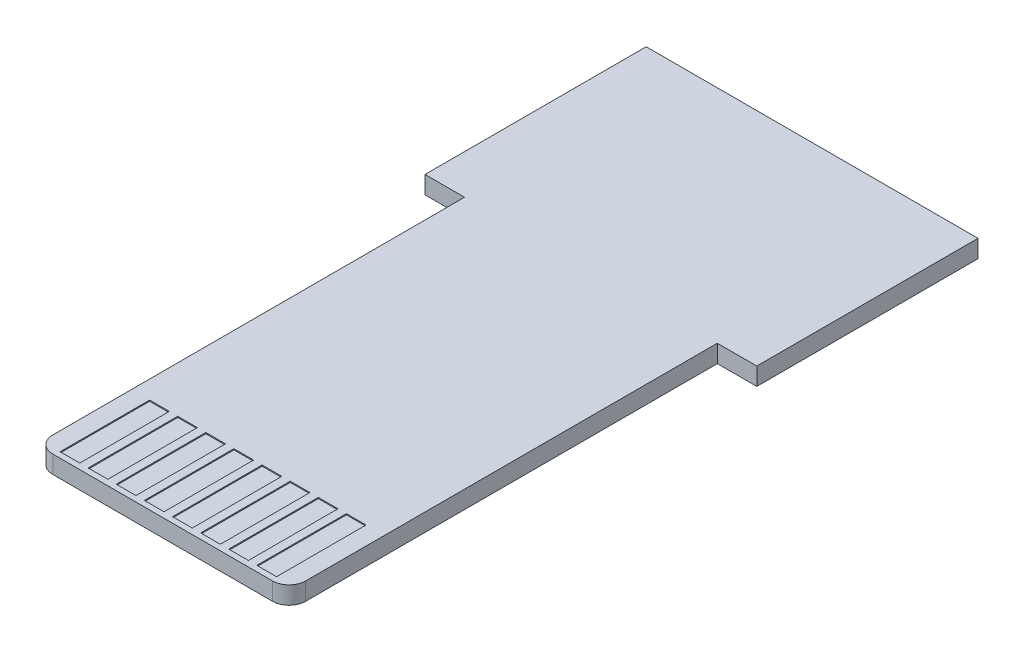
SolidWorks part; units mm, degrees
material "丙烯酸(中高冲击)"
ref_plane "前视基准面" through (0, 0, 0) normal (0, 0, 1) x (1, 0, 0)
ref_plane "上视基准面" through (0, 0, 0) normal (0, 1, 0) x (1, 0, 0)
ref_plane "右视基准面" through (0, 0, 0) normal (1, 0, 0) x (0, 0, -1)
other "Configuration Table"
sketch "草图1" plane through (0, 0, 0) normal (0, 1, 0) x (1, 0, 0)
  line L0 (11.43, -10) -> (15, -10)
  line L1 (-15, 10) -> (15, 10)
  line L2 (-15, 10) -> (-15, -10)
  line L3 (-15, -10) -> (-11.43, -10)
  line L4 (15, 10) -> (15, -10)
  line L5 (-15, 10) -> (15, -10) construction
  line L6 (-15, -10) -> (15, 10) construction
  line L8 (-11.43, -10) -> (-11.43, -47.22)
  line L9 (-9.93, -48.72) -> (9.93, -48.72)
  line L10 (11.43, -10) -> (11.43, -47.22)
  arc A0 (-11.43, -47.22) -> (-9.93, -48.72) centre (-9.93, -47.22) ccw
  arc A1 (9.93, -48.72) -> (11.43, -47.22) centre (9.93, -47.22) ccw
  point P0 (0, 0)
  point P10 (0, -48.72)
  dimension "D5" = 3
  dimension "D6" = 3
  dimension "D1" = 30
  dimension "D2" = 20
  dimension "D3" = 38.72
  dimension "D4" = 22.86
extrude "凸台-拉伸1" add sketch "草图1" along normal blind 1.6
sketch "草图3" plane through (0, 0, 0) normal (0, 1, 0) x (1, 0, 0)
  line L0 (0, -1000) -> (0, 49000) construction
  line L1 (-9.93, -48.72) -> (9.93, -48.72) construction
  line L2 (-2.165, -40.11) -> (-0.385, -40.11)
  line L3 (-2.165, -40.11) -> (-2.165, -48.21)
  line L4 (-2.165, -48.21) -> (-0.385, -48.21)
  line L5 (-0.385, -40.11) -> (-0.385, -48.21)
  line L6 (0.385, -40.11) -> (2.165, -40.11)
  line L7 (0.385, -40.11) -> (0.385, -48.21)
  line L8 (0.385, -48.21) -> (2.165, -48.21)
  line L9 (2.165, -40.11) -> (2.165, -48.21)
  line L10 (-4.705, -40.11) -> (-2.925, -40.11)
  line L11 (-4.705, -40.11) -> (-4.705, -48.21)
  line L12 (-4.705, -48.21) -> (-2.925, -48.21)
  line L13 (-2.925, -40.11) -> (-2.925, -48.21)
  line L14 (-7.245, -40.11) -> (-5.465, -40.11)
  line L15 (-7.245, -40.11) -> (-7.245, -48.21)
  line L16 (-7.245, -48.21) -> (-5.465, -48.21)
  line L17 (-5.465, -40.11) -> (-5.465, -48.21)
  line L18 (-9.785, -40.11) -> (-8.005, -40.11)
  line L19 (-9.785, -40.11) -> (-9.785, -48.21)
  line L20 (-9.785, -48.21) -> (-8.005, -48.21)
  line L21 (-8.005, -40.11) -> (-8.005, -48.21)
  line L22 (-2.165, -40.11) -> (-4.705, -40.11) construction
  line L23 (2.925, -40.11) -> (4.705, -40.11)
  line L24 (2.925, -40.11) -> (2.925, -48.21)
  line L25 (2.925, -48.21) -> (4.705, -48.21)
  line L26 (4.705, -40.11) -> (4.705, -48.21)
  line L27 (5.465, -40.11) -> (7.245, -40.11)
  line L28 (5.465, -40.11) -> (5.465, -48.21)
  line L29 (5.465, -48.21) -> (7.245, -48.21)
  line L30 (7.245, -40.11) -> (7.245, -48.21)
  line L31 (8.005, -40.11) -> (9.785, -40.11)
  line L32 (8.005, -40.11) -> (8.005, -48.21)
  line L33 (8.005, -48.21) -> (9.785, -48.21)
  line L34 (9.785, -40.11) -> (9.785, -48.21)
  line L35 (0.385, -40.11) -> (2.925, -40.11) construction
  dimension "D1" = 1.78
  dimension "D2" = 8.1
  dimension "D3" = 8.1
  dimension "D4" = 1.78
  dimension "D5" = 0.51
  dimension "D6" = 0.51
  dimension "D7" = 0.77
  dimension "D8" = 4
  dimension "D9" = 2.54
  dimension "D11" = 2.54
  dimension "D10" = 4
extrude "切除-拉伸1" cut sketch "草图3" against normal blind 0.1 from surface at 1.6 starting at face at (0, 1.6, 21.2501)
sketch "草图4" plane through (0, 0, 0) normal (0, 1, 0) x (1, 0, 0)
  line L4 (2.165, -40.11) -> (0.385, -40.11)
  line L5 (2.165, -48.21) -> (2.165, -40.11)
  line L6 (0.385, -48.21) -> (2.165, -48.21)
  line L7 (0.385, -40.11) -> (0.385, -48.21)
  line L8 (2.165, -40.11) -> (0.385, -40.11)
  line L9 (2.165, -48.21) -> (2.165, -40.11)
  line L10 (0.385, -48.21) -> (2.165, -48.21)
  line L11 (0.385, -40.11) -> (0.385, -48.21)
  line L12 (-0.385, -40.11) -> (-2.165, -40.11)
  line L13 (-0.385, -48.21) -> (-0.385, -40.11)
  line L14 (-2.165, -48.21) -> (-0.385, -48.21)
  line L15 (-2.165, -40.11) -> (-2.165, -48.21)
  line L16 (-0.385, -40.11) -> (-2.165, -40.11)
  line L17 (-0.385, -48.21) -> (-0.385, -40.11)
  line L18 (-2.165, -48.21) -> (-0.385, -48.21)
  line L19 (-2.165, -40.11) -> (-2.165, -48.21)
  line L20 (-8.005, -40.11) -> (-9.785, -40.11)
  line L21 (-8.005, -48.21) -> (-8.005, -40.11)
  line L22 (-9.785, -48.21) -> (-8.005, -48.21)
  line L23 (-9.785, -40.11) -> (-9.785, -48.21)
  line L24 (-8.005, -40.11) -> (-9.785, -40.11)
  line L25 (-8.005, -48.21) -> (-8.005, -40.11)
  line L26 (-9.785, -48.21) -> (-8.005, -48.21)
  line L27 (-9.785, -40.11) -> (-9.785, -48.21)
  line L28 (-5.465, -40.11) -> (-7.245, -40.11)
  line L29 (-5.465, -48.21) -> (-5.465, -40.11)
  line L30 (-7.245, -48.21) -> (-5.465, -48.21)
  line L31 (-7.245, -40.11) -> (-7.245, -48.21)
  line L32 (-5.465, -40.11) -> (-7.245, -40.11)
  line L33 (-5.465, -48.21) -> (-5.465, -40.11)
  line L34 (-7.245, -48.21) -> (-5.465, -48.21)
  line L35 (-7.245, -40.11) -> (-7.245, -48.21)
  line L36 (-2.925, -40.11) -> (-4.705, -40.11)
  line L37 (-4.705, -40.11) -> (-4.705, -48.21)
  line L38 (-4.705, -48.21) -> (-2.925, -48.21)
  line L39 (-2.925, -48.21) -> (-2.925, -40.11)
  line L40 (-2.925, -40.11) -> (-4.705, -40.11)
  line L41 (-4.705, -40.11) -> (-4.705, -48.21)
  line L42 (-4.705, -48.21) -> (-2.925, -48.21)
  line L43 (-2.925, -48.21) -> (-2.925, -40.11)
  line L44 (9.785, -40.11) -> (8.005, -40.11)
  line L45 (9.785, -48.21) -> (9.785, -40.11)
  line L46 (8.005, -48.21) -> (9.785, -48.21)
  line L47 (8.005, -40.11) -> (8.005, -48.21)
  line L48 (9.785, -40.11) -> (8.005, -40.11)
  line L49 (9.785, -48.21) -> (9.785, -40.11)
  line L50 (8.005, -48.21) -> (9.785, -48.21)
  line L51 (8.005, -40.11) -> (8.005, -48.21)
  line L52 (7.245, -40.11) -> (5.465, -40.11)
  line L53 (7.245, -48.21) -> (7.245, -40.11)
  line L54 (5.465, -48.21) -> (7.245, -48.21)
  line L55 (5.465, -40.11) -> (5.465, -48.21)
  line L56 (7.245, -40.11) -> (5.465, -40.11)
  line L57 (7.245, -48.21) -> (7.245, -40.11)
  line L58 (5.465, -48.21) -> (7.245, -48.21)
  line L59 (5.465, -40.11) -> (5.465, -48.21)
  line L60 (4.705, -40.11) -> (2.925, -40.11)
  line L61 (2.925, -40.11) -> (2.925, -48.21)
  line L62 (2.925, -48.21) -> (4.705, -48.21)
  line L63 (4.705, -48.21) -> (4.705, -40.11)
  line L64 (4.705, -40.11) -> (2.925, -40.11)
  line L65 (2.925, -40.11) -> (2.925, -48.21)
  line L66 (2.925, -48.21) -> (4.705, -48.21)
  line L67 (4.705, -48.21) -> (4.705, -40.11)
  dimension "D1" = 0
  dimension "D2" = 0
  dimension "D3" = 0
  dimension "D4" = 0
  dimension "D5" = 0
  dimension "D6" = 0
  dimension "D7" = 0
  dimension "D8" = 0
extrude "切除-拉伸2" cut sketch "草图4" along normal blind 0.1 from surface at 0 starting at face at (0, 0, 21.2501)
